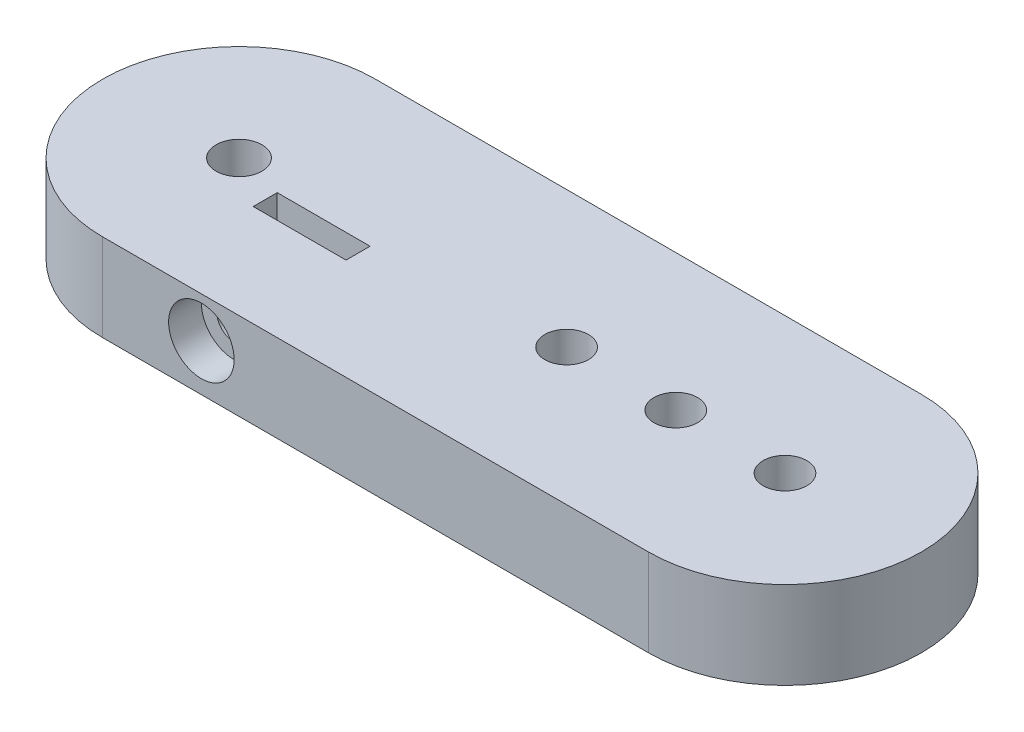
SolidWorks part; units mm, degrees
ref_plane "前视基准面" through (0, 0, 0) normal (0, 0, 1) x (1, 0, 0)
ref_plane "上视基准面" through (0, 0, 0) normal (0, 1, 0) x (1, 0, 0)
ref_plane "右视基准面" through (0, 0, 0) normal (1, 0, 0) x (0, 0, -1)
sketch "草图1" plane through (0, 0, 0) normal (0, 1, 0) x (1, 0, 0)
  line L0 (0, 0) -> (50, 0) construction
  line L1 (0, 12.5) -> (50, 12.5)
  line L2 (0, -12.5) -> (50, -12.5)
  line L3 (0, 0) -> (4.5, 0) construction
  line L10 (0, 2.1) -> (0, -3.2) construction
  line L11 (4.5, -3.2) -> (13, -3.2)
  line L12 (4.5, -3.2) -> (4.5, -1)
  line L13 (4.5, -1) -> (13, -1)
  line L14 (13, -1) -> (13, -3.2)
  arc A0 (0, 12.5) -> (0, -12.5) centre (0, 0) ccw
  arc A1 (50, -12.5) -> (50, 12.5) centre (50, 0) ccw
  circle A2 centre (0, 0) radius 2.1
  circle A3 centre (50, 0) radius 2
  point P3 (25, 0)
  dimension "D3" = 4.2
  dimension "D8" = 4
  dimension "D1" = 50
  dimension "D2" = 25
  dimension "D4" = 4.5
  dimension "D5" = 2.2
  dimension "D9" = 5.3
extrude "凸台-拉伸1" add sketch "草图1" along normal blind 8
sketch "草图2" plane through (0, 8, 0) normal (0, 1, 0) x (1, 0, 0)
  line L0 (0, 0) -> (40, 0) construction
  line L1 (0, 0) -> (30, 0) construction
  line L2 (0, 0) -> (50, 0) construction
  circle A0 centre (40, 0) radius 2
  circle A1 centre (30, 0) radius 2
  circle A2 centre (50, 0) radius 2
  dimension "D2" = 4
  dimension "D4" = 4
  dimension "D6" = 4
  dimension "D1" = 40
  dimension "D3" = 30
  dimension "D5" = 50
extrude "切除-拉伸2" cut sketch "草图2" against normal blind 8
sketch "草图3" plane through (0, 0, 12.5) normal (0, 0, 1) x (1, 0, 0)
  circle A0 centre (9.0519, 4.2714) radius 1.6
  dimension "D1" = 3.2
extrude "切除-拉伸3" cut sketch "草图3" against normal blind 10
sketch "草图4" plane through (0, 0, 12.5) normal (0, 0, 1) x (1, 0, 0)
  circle A0 centre (9.0519, 4.2714) radius 3
  dimension "D1" = 6
extrude "切除-拉伸4" cut sketch "草图4" against normal blind 3
